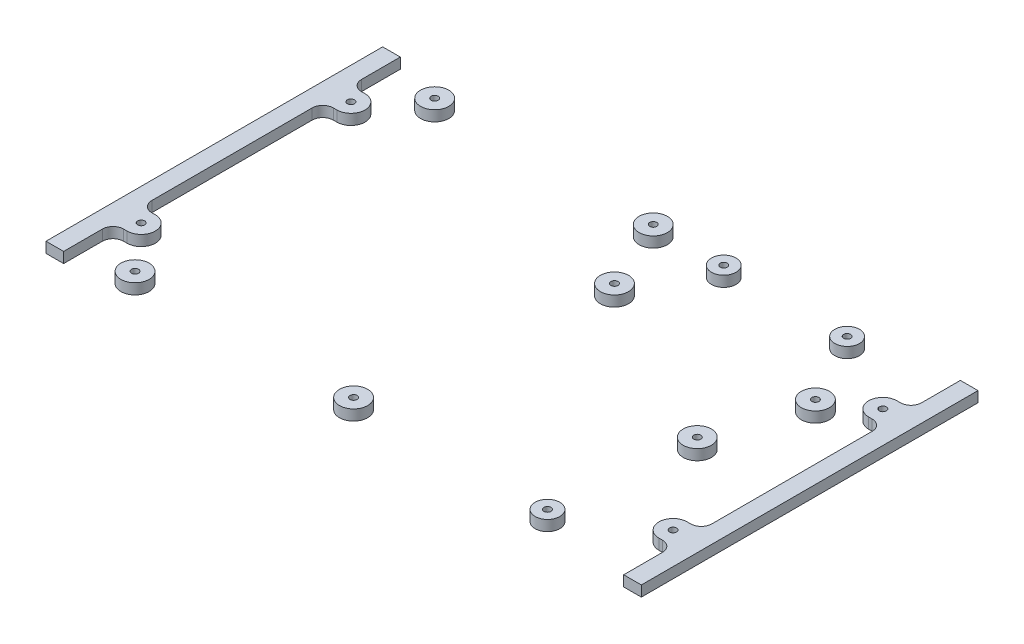
SolidWorks part; units mm, degrees
ref_plane "Front Plane" through (0, 0, 0) normal (0, 0, 1) x (1, 0, 0)
ref_plane "Top Plane" through (0, 0, 0) normal (0, 1, 0) x (1, 0, 0)
ref_plane "Right Plane" through (0, 0, 0) normal (1, 0, 0) x (0, 0, -1)
sketch "Sketch1" plane through (0, 38, 0) normal (0, 1, 0) x (1, 0, 0)
  line L10 (-53.875, 4.25) -> (-53.875, -91.25)
  line L11 (-53.875, -91.25) -> (-48.875, -91.25)
  line L12 (-48.875, -91.25) -> (-48.875, -80.25)
  line L13 (-45.875, -77.25) -> (-44.875, -77.25)
  line L14 (-44.875, -69.25) -> (-45.875, -69.25)
  line L15 (-48.875, -66.25) -> (-48.875, -20.75)
  line L16 (-45.875, -17.75) -> (-44.875, -17.75)
  line L17 (-44.875, -9.75) -> (-45.875, -9.75)
  line L18 (-48.875, -6.75) -> (-48.875, 4.25)
  line L19 (-48.875, 4.25) -> (-53.875, 4.25)
  line L20 (-53.875, 4.25) -> (-53.875, -91.25)
  line L21 (-53.875, -91.25) -> (-48.875, -91.25)
  line L22 (-48.875, -91.25) -> (-48.875, -80.25)
  line L23 (-45.875, -77.25) -> (-44.875, -77.25)
  line L24 (-44.875, -69.25) -> (-45.875, -69.25)
  line L25 (-48.875, -66.25) -> (-48.875, -20.75)
  line L26 (-45.875, -17.75) -> (-44.875, -17.75)
  line L27 (-44.875, -9.75) -> (-45.875, -9.75)
  line L28 (-48.875, -6.75) -> (-48.875, 4.25)
  line L29 (-48.875, 4.25) -> (-53.875, 4.25)
  line L30 (110, 4.25) -> (110, -6.75)
  line L31 (107, -9.75) -> (106, -9.75)
  line L32 (106, -17.75) -> (107, -17.75)
  line L33 (110, -20.75) -> (110, -66.25)
  line L34 (107, -69.25) -> (106, -69.25)
  line L35 (106, -77.25) -> (107, -77.25)
  line L36 (110, -80.25) -> (110, -91.25)
  line L37 (110, -91.25) -> (115, -91.25)
  line L38 (115, -91.25) -> (115, 4.25)
  line L39 (115, 4.25) -> (110, 4.25)
  line L40 (110, 4.25) -> (110, -6.75)
  line L41 (107, -9.75) -> (106, -9.75)
  line L42 (106, -17.75) -> (107, -17.75)
  line L43 (110, -20.75) -> (110, -66.25)
  line L44 (107, -69.25) -> (106, -69.25)
  line L45 (106, -77.25) -> (107, -77.25)
  line L46 (110, -80.25) -> (110, -91.25)
  line L47 (110, -91.25) -> (115, -91.25)
  line L48 (115, -91.25) -> (115, 4.25)
  line L49 (115, 4.25) -> (110, 4.25)
  circle A0 centre (-44.875, -13.75) radius 1 construction
  circle A1 centre (-44.875, -13.75) radius 1
  circle A2 centre (106, -13.75) radius 1 construction
  circle A3 centre (106, -73.25) radius 1 construction
  circle A4 centre (-44.875, -73.25) radius 1 construction
  circle A5 centre (106, -13.75) radius 1
  arc A6 (-45.875, -77.25) -> (-48.875, -80.25) centre (-45.875, -80.25) ccw
  arc A7 (-44.875, -77.25) -> (-44.875, -69.25) centre (-44.875, -73.25) ccw
  arc A8 (-48.875, -66.25) -> (-45.875, -69.25) centre (-45.875, -66.25) ccw
  arc A9 (-45.875, -17.75) -> (-48.875, -20.75) centre (-45.875, -20.75) ccw
  arc A10 (-44.875, -17.75) -> (-44.875, -9.75) centre (-44.875, -13.75) ccw
  arc A11 (-48.875, -6.75) -> (-45.875, -9.75) centre (-45.875, -6.75) ccw
  arc A12 (-45.875, -77.25) -> (-48.875, -80.25) centre (-45.875, -80.25) ccw
  arc A13 (-44.875, -77.25) -> (-44.875, -69.25) centre (-44.875, -73.25) ccw
  arc A14 (-48.875, -66.25) -> (-45.875, -69.25) centre (-45.875, -66.25) ccw
  arc A15 (-45.875, -17.75) -> (-48.875, -20.75) centre (-45.875, -20.75) ccw
  arc A16 (-44.875, -17.75) -> (-44.875, -9.75) centre (-44.875, -13.75) ccw
  arc A17 (-48.875, -6.75) -> (-45.875, -9.75) centre (-45.875, -6.75) ccw
  arc A18 (107, -9.75) -> (110, -6.75) centre (107, -6.75) ccw
  arc A19 (106, -9.75) -> (106, -17.75) centre (106, -13.75) ccw
  arc A20 (110, -20.75) -> (107, -17.75) centre (107, -20.75) ccw
  arc A21 (107, -69.25) -> (110, -66.25) centre (107, -66.25) ccw
  arc A22 (106, -69.25) -> (106, -77.25) centre (106, -73.25) ccw
  arc A23 (110, -80.25) -> (107, -77.25) centre (107, -80.25) ccw
  arc A24 (107, -9.75) -> (110, -6.75) centre (107, -6.75) ccw
  arc A25 (106, -9.75) -> (106, -17.75) centre (106, -13.75) ccw
  arc A26 (110, -20.75) -> (107, -17.75) centre (107, -20.75) ccw
  arc A27 (107, -69.25) -> (110, -66.25) centre (107, -66.25) ccw
  arc A28 (106, -69.25) -> (106, -77.25) centre (106, -73.25) ccw
  arc A29 (110, -80.25) -> (107, -77.25) centre (107, -80.25) ccw
  circle A30 centre (106, -73.25) radius 1
  circle A31 centre (-44.875, -73.25) radius 1
  circle A32 centre (-33.875, -86) radius 1 construction
  circle A33 centre (-33.875, -86) radius 4 construction
  circle A34 centre (28.125, -86) radius 1 construction
  circle A35 centre (28.125, -86) radius 4 construction
  circle A36 centre (28.125, -1) radius 1 construction
  circle A37 centre (28.125, -1) radius 4 construction
  circle A38 centre (-33.875, -1) radius 1 construction
  circle A39 centre (-33.875, -1) radius 4 construction
  circle A40 centre (-33.875, -86) radius 1
  circle A41 centre (-33.875, -86) radius 4
  circle A42 centre (28.125, -86) radius 1
  circle A43 centre (28.125, -86) radius 4
  circle A44 centre (28.125, -1) radius 1
  circle A45 centre (28.125, -1) radius 4
  circle A46 centre (-33.875, -1) radius 1
  circle A47 centre (-33.875, -1) radius 4
  dimension "D1" = 0
  dimension "D2" = 0
extrude "LEVEL 2 interface and amp screwholes" add sketch "Sketch1" along normal blind 3
sketch "Sketch2" plane through (0, 41, 0) normal (0, 1, 0) x (1, 0, 0)
  line L0 (48.125, -1) -> (28.125, -1) construction
  line L1 (48.125, -1) -> (83.125, -1) construction
  line L2 (48.125, -1) -> (48.125, -86) construction
  line L3 (48.125, -86) -> (83.125, -86) construction
  line L4 (83.125, -1) -> (83.125, -86) construction
  circle A0 centre (83.125, -1) radius 1
  circle A1 centre (48.125, -1) radius 1
  circle A2 centre (83.125, -86) radius 1
  circle A3 centre (48.125, -1) radius 3.5
  circle A4 centre (83.125, -1) radius 3.5
  circle A5 centre (83.125, -86) radius 3.5
  dimension "D3" = 2
  dimension "D1" = 35
  dimension "D2" = 85
  dimension "D5" = 20
  dimension "D4" = 2.5
extrude "Sound card screwholes" add sketch "Sketch2" against normal up to surface (3 mm away) separate body up to face at (-47.4053, 38, 43.5)
sketch "Sketch3" plane through (0, 41, 0) normal (0, 1, 0) x (1, 0, 0)
  line L0 (37.125, -21) -> (94.125, -21) construction
  line L1 (44.625, -47) -> (86.625, -47) construction
  line L2 (48.125, -1) -> (83.125, -1) construction
  circle A0 centre (28.125, -1) radius 1 construction
  circle A1 centre (37.125, -21) radius 1
  circle A2 centre (94.125, -21) radius 1
  circle A3 centre (86.625, -47) radius 1
  circle A4 centre (94.125, -21) radius 4
  circle A5 centre (86.625, -47) radius 4
  circle A6 centre (37.125, -21) radius 4
  point P4 (65.625, -47)
  point P5 (65.625, -21)
  point P12 (65.625, -1)
  dimension "D5" = 2
  dimension "D1" = 57
  dimension "D2" = 42
  dimension "D3" = 26
  dimension "D4" = 20
  dimension "D6" = 3
extrude "Boss-Extrude3" add sketch "Sketch3" against normal up to surface (3 mm away) separate body up to face at (108.5303, 38, 43.5)
